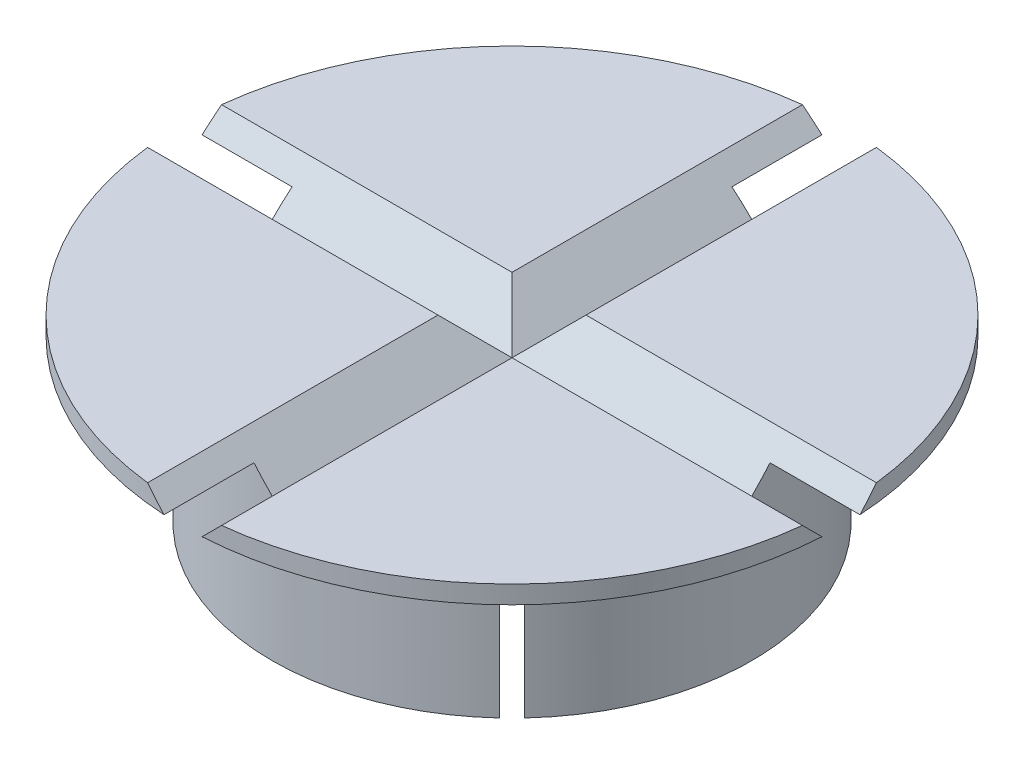
SolidWorks part; units mm, degrees
ref_plane "Front Plane" through (0, 0, 0) normal (0, 0, 1) x (1, 0, 0)
ref_plane "Top Plane" through (0, 0, 0) normal (0, 1, 0) x (1, 0, 0)
ref_plane "Right Plane" through (0, 0, 0) normal (1, 0, 0) x (0, 0, -1)
sketch "Sketch1" plane through (0, 0, 0) normal (1, 0, 0) x (0, 0, -1)
  line L0 (0, 0) -> (26.7, 0)
  line L1 (26.7, 0) -> (26.7, 18)
  line L2 (26.7, 18) -> (36.7, 18)
  line L3 (36.7, 18) -> (36.7, 20)
  line L4 (36.7, 20) -> (0, 20)
  line L5 (0, 20) -> (0, 0)
  dimension "D1" = 26.7
  dimension "D2" = 10
  dimension "D3" = 20
  dimension "D4" = 2
revolve "Revolve1" add sketch "Sketch1" angle 360 about L5
sketch "Sketch2" plane through (0, 0, 0) normal (0, 0, 1) x (1, 0, 0)
  line L0 (4.1213, 20) -> (0, 15.8787)
  line L1 (0, 15.8787) -> (-4.1213, 20)
  line L2 (-4.1213, 20) -> (4.1213, 20)
  line L3 (-2.1213, 18) -> (2.1213, 18) construction
  dimension "D1" = 20
  dimension "D2" = 18
  dimension "D3" = 3
extrude "Cut-Extrude1" cut sketch "Sketch2" against normal through all both and the other way through all
pattern_circular "CirPattern1" count 4 over 360 about axis through (0, 0, 0) along (0, 1, 0) of "Cut-Extrude1"
sketch "Sketch3" plane through (0, 0, 0) normal (0, -1, 0) x (1, 0, 0)
  circle A0 centre (0, 0) radius 23.75
  dimension "D1" = 47.5
extrude "Cut-Extrude2" cut sketch "Sketch3" against normal blind 12
sketch "Sketch4" plane through (0, 0, 0) normal (0, 1, 0) x (1, 0, 0)
  line L0 (-25.2341, -26.6483) -> (0, -1.4142)
  line L1 (0, 0) -> (0, -26.7) construction
  line L2 (-26.6483, -25.2341) -> (-1.4142, 0)
  line L3 (-26.7, 0) -> (0, 0) construction
  line L4 (-1.4142, 0) -> (0, -1.4142)
  arc A0 (-36.4679, -4.1213) -> (-4.1213, -36.4679) centre (0, 0) ccw construction
  arc A1 (-25.2341, -26.6483) -> (-26.6483, -25.2341) centre (0, 0) cw
  dimension "D1" = 2
  dimension "D2" = 45
extrude "Cut-Extrude3" cut sketch "Sketch4" along normal blind 12 contours L0 L4 L2 A1
pattern_circular "CirPattern2" count 4 over 360 about axis through (0, 0, 0) along (0, 1, 0) of "Cut-Extrude3"
sketch "Sketch5" plane through (0, 12, 0) normal (0, -1, 0) x (1, 0, 0)
  circle A0 centre (0, 0) radius 5
  circle A1 centre (0, 0) radius 2.35
  dimension "D1" = 10
  dimension "D2" = 4.7
extrude "Boss-Extrude1" add sketch "Sketch5" along normal blind 14
chamfer "Chamfer1" distance 1 angle 45 1 edges at (0, -2, -2.35)
chamfer "Chamfer2" distance 5 angle 45 1 edges at (0, 12, -5)
